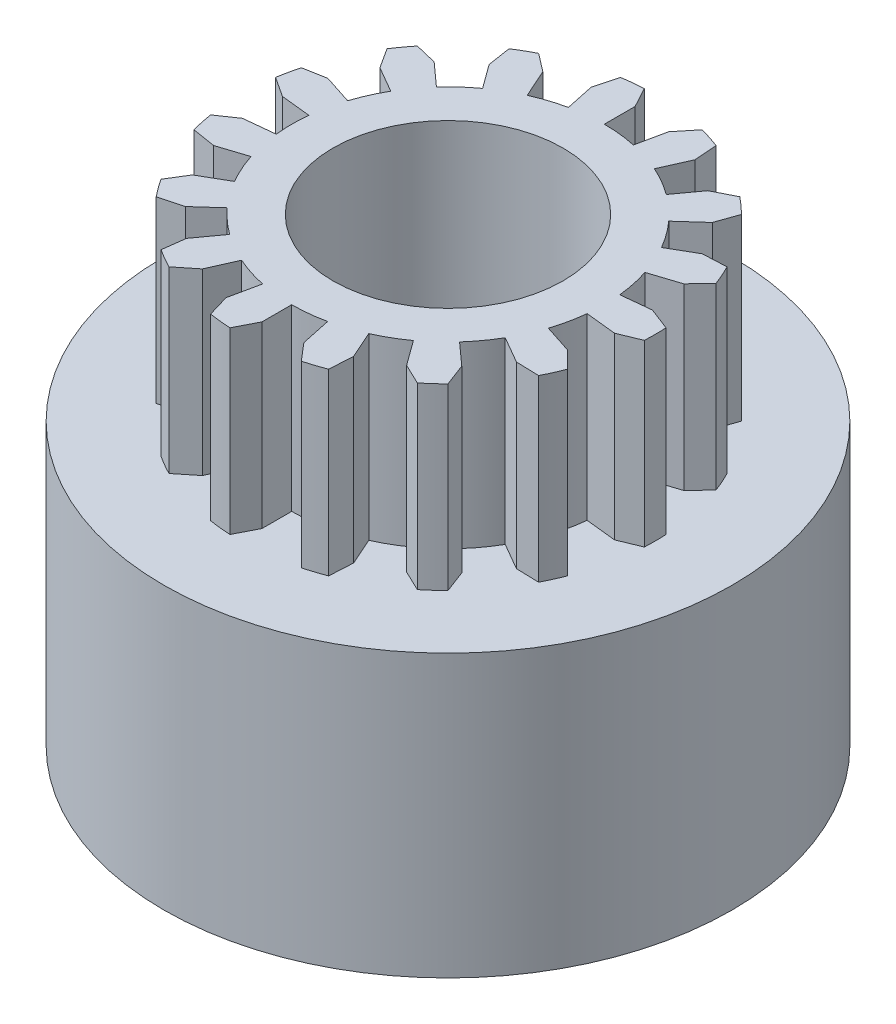
SolidWorks part; units mm, degrees
ref_plane "Front Plane" through (0, 0, 0) normal (0, 0, 1) x (1, 0, 0)
ref_plane "Top Plane" through (0, 0, 0) normal (0, 1, 0) x (1, 0, 0)
ref_plane "Right Plane" through (0, 0, 0) normal (1, 0, 0) x (0, 0, -1)
sketch "Sketch1" plane through (0, 0, 0) normal (0, 1, 0) x (1, 0, 0)
  circle A0 centre (0, 0) radius 11.1125
  dimension "D1" = 22.225
extrude "Boss-Extrude1" add sketch "Sketch1" along normal blind 18
sketch "Sketch2" plane through (0, 18, 0) normal (0, 1, 0) x (1, 0, 0)
  line L0 (10.1518, 4.5199) -> (7.4111, 3.2997)
  line L1 (8.1125, 0) -> (11.1125, 0)
  line L2 (5.8133, 1.8889) -> (6.9591, 2.2611)
  line L3 (6.079, 0.6389) -> (7.2342, 0.7603)
  line L4 (7.5737, 2.9073) -> (6.9591, 2.2611)
  line L5 (8.1014, 0.4246) -> (7.2342, 0.7603)
  circle A0 centre (0, 0) radius 11.1125 construction
  arc A1 (11.1125, 0) -> (10.1518, 4.5199) centre (0, 0) ccw
  arc A2 (8.1125, 0) -> (8.1014, 0.4246) centre (0, 0) ccw
  arc A3 (6.079, 0.6389) -> (5.8133, 1.8889) centre (0, 0) ccw
  arc A4 (7.5737, 2.9073) -> (7.4111, 3.2997) centre (0, 0) ccw
  dimension "D1" = 3
  dimension "D3" = 2
  dimension "D2" = 24
  dimension "D4" = 12
  dimension "D5" = 6
extrude "Cut-Extrude2" cut sketch "Sketch2" against normal blind 7
pattern_circular "CirPattern1" count 15 every 24 about axis through (0, 0, 0) along (0, 1, 0) of "Cut-Extrude2"
sketch "Sketch3" plane through (0, 0, 0) normal (0, -1, 0) x (1, 0, 0)
  circle A0 centre (0, 0) radius 6.5
  dimension "D1" = 13
extrude "Cut-Extrude3" cut sketch "Sketch3" against normal blind 3
sketch "Sketch4" plane through (0, 3, 0) normal (0, -1, 0) x (1, 0, 0)
  circle A0 centre (0, 0) radius 4.5
  dimension "D1" = 9
extrude "Cut-Extrude4" cut sketch "Sketch4" against normal through all
